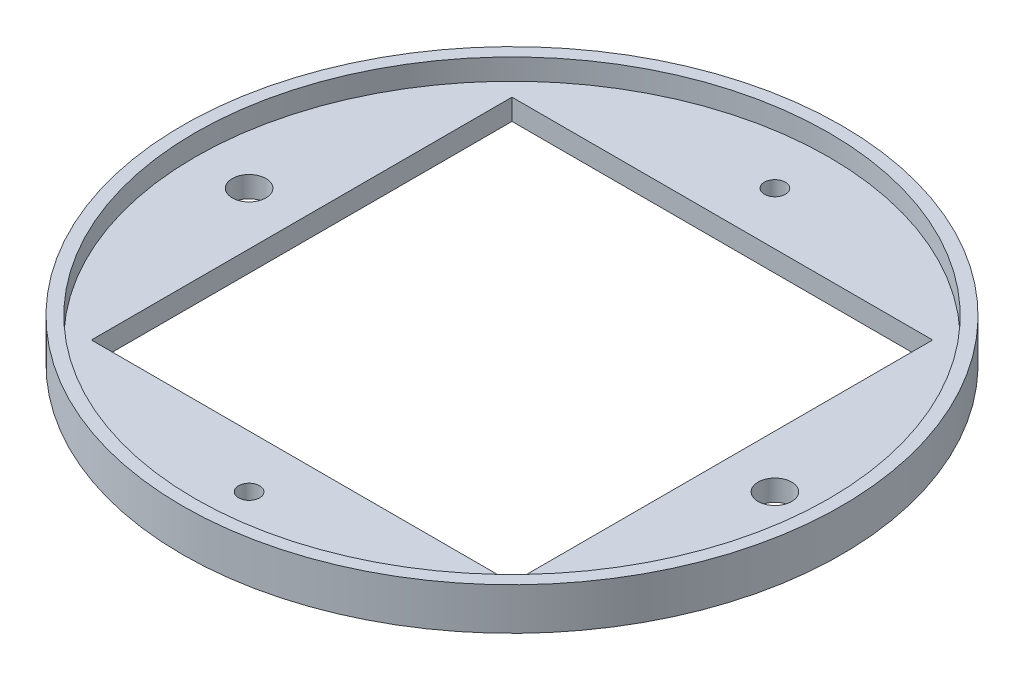
SolidWorks part; units mm, degrees
material "Custom Plastic"
ref_plane "Front Plane" through (0, 0, 0) normal (0, 0, 1) x (1, 0, 0)
ref_plane "Top Plane" through (0, 0, 0) normal (0, 1, 0) x (1, 0, 0)
ref_plane "Right Plane" through (0, 0, 0) normal (1, 0, 0) x (0, 0, -1)
sketch "Sketch1" plane through (0, 0, 0) normal (0, 1, 0) x (1, 0, 0)
  line L1 (-50, -50) -> (50, -50)
  line L2 (-50, -50) -> (-50, 50)
  line L3 (-50, 50) -> (50, 50)
  line L4 (50, -50) -> (50, 50)
  line L5 (-50, -50) -> (50, 50) construction
  line L6 (-50, 50) -> (50, -50) construction
  circle A0 centre (0, 0) radius 78.35
  circle A1 centre (0, 0) radius 62.5 construction
  circle A2 centre (-62.5, 0) radius 4
  circle A3 centre (62.5, 0) radius 4
  circle A4 centre (0, 62.5) radius 2.5
  circle A5 centre (0, -62.5) radius 2.5
  dimension "D1" = 156.7
  dimension "D3" = 125
  dimension "D4" = 5
  dimension "D5" = 5
  dimension "D6" = 8
  dimension "D7" = 8
  dimension "D2" = 100
extrude "Boss-Extrude1" add sketch "Sketch1" along normal blind 5
sketch "Sketch2" plane through (0, 5, 0) normal (0, 1, 0) x (1, 0, 0)
  circle A0 centre (0, 0) radius 78.35 construction
  circle A1 centre (0, 0) radius 78.35
  circle A2 centre (0, 0) radius 75.35
  dimension "D1" = 3
extrude "Boss-Extrude2" add sketch "Sketch2" along normal blind 5
